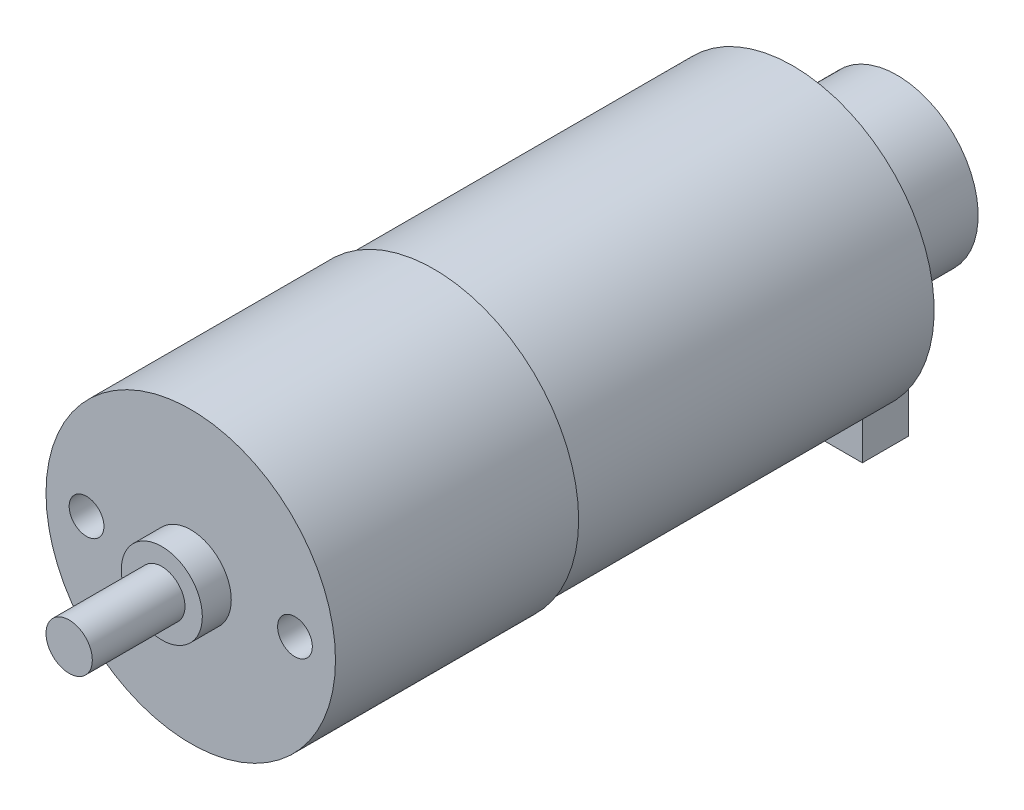
SolidWorks part; units mm, degrees
ref_plane "Front Plane" through (0, 0, 0) normal (0, 0, 1) x (1, 0, 0)
ref_plane "Top Plane" through (0, 0, 0) normal (0, 1, 0) x (1, 0, 0)
ref_plane "Right Plane" through (0, 0, 0) normal (1, 0, 0) x (0, 0, -1)
sketch "Sketch1" plane through (0, 0, 0) normal (0, 0, 1) x (1, 0, 0)
  circle A0 centre (0, 0) radius 12.2
  dimension "D1" = 24.4
extrude "Boss-Extrude1" add sketch "Sketch1" along normal blind 31
sketch "Sketch2" plane through (0, 0, 31) normal (0, 0, 1) x (1, 0, 0)
  circle A0 centre (0, 0) radius 12.5
  dimension "D1" = 25
extrude "Boss-Extrude2" add sketch "Sketch2" along normal blind 21
sketch "Sketch3" plane through (0, 0, 52) normal (0, 0, 1) x (1, 0, 0)
  circle A0 centre (0, 0) radius 3.5
  dimension "D1" = 7
extrude "Boss-Extrude3" add sketch "Sketch3" along normal blind 2.5
sketch "Sketch4" plane through (0, 0, 54.5) normal (0, 0, 1) x (1, 0, 0)
  circle A0 centre (0, 0) radius 2
  dimension "D1" = 4
extrude "Boss-Extrude4" add sketch "Sketch4" along normal blind 8
sketch "Sketch5" plane through (0, 0, 0) normal (0, 0, -1) x (-1, 0, 0)
  circle A0 centre (0, 0) radius 7
  dimension "D1" = 14
extrude "Boss-Extrude5" add sketch "Sketch5" along normal blind 9
sketch "Sketch6" plane through (0, 0, 0) normal (0, 0, -1) x (-1, 0, 0)
  line L1 (-6, -7.5) -> (6, -7.5)
  line L2 (-6, -7.5) -> (-6, -14.5)
  line L3 (-6, -14.5) -> (6, -14.5)
  line L4 (6, -7.5) -> (6, -14.5)
  circle A0 centre (0, 0) radius 7 construction
  point P4 (0, -7.5)
  dimension "D3" = 7.5
  dimension "D1" = 7
  dimension "D2" = 12
extrude "Boss-Extrude6" add sketch "Sketch6" along normal blind 4
sketch "Sketch7" plane through (0, 0, 52) normal (0, 0, 1) x (1, 0, 0)
  line L0 (0, 0) -> (-9, 0) construction
  line L1 (0, 0) -> (9, 0) construction
  circle A0 centre (-9, 0) radius 1.5
  circle A1 centre (9, 0) radius 1.5
  dimension "D1" = 3
  dimension "D2" = 9
extrude "Cut-Extrude1" cut sketch "Sketch7" against normal blind 7
